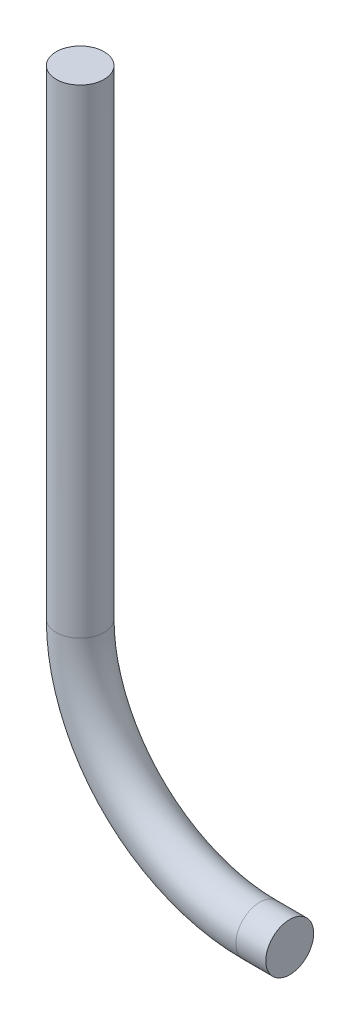
SolidWorks part; units mm, degrees
ref_plane "Front Plane" through (0, 0, 0) normal (0, 0, 1) x (1, 0, 0)
ref_plane "Top Plane" through (0, 0, 0) normal (0, 1, 0) x (1, 0, 0)
ref_plane "Right Plane" through (0, 0, 0) normal (1, 0, 0) x (0, 0, -1)
sketch "Sketch1" plane through (0, 0, 0) normal (0, 0, 1) x (1, 0, 0)
  line L0 (0, 0) -> (-5, 0)
  line L1 (-35, 30) -> (-35, 110)
  arc A0 (-5, 0) -> (-35, 30) centre (-5, 30) cw
  dimension "D1" = 30
  dimension "D2" = 5
  dimension "D3" = 80
sketch "Sketch2" plane through (0, 0, 0) normal (1, 0, 0) x (0, 0, -1)
  circle A0 centre (0, 0) radius 4
  dimension "D1" = 8
sweep "Sweep1" add profiles "Sketch2" path "Sketch1"
